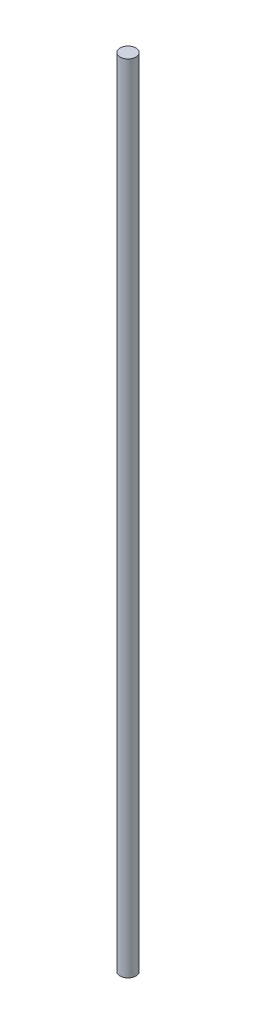
SolidWorks part; units mm, degrees
ref_plane "Front Plane" through (0, 0, 0) normal (0, 0, 1) x (1, 0, 0)
ref_plane "Top Plane" through (0, 0, 0) normal (0, 1, 0) x (1, 0, 0)
ref_plane "Right Plane" through (0, 0, 0) normal (1, 0, 0) x (0, 0, -1)
sketch "Sketch1" plane through (0, 0, 0) normal (0, 1, 0) x (1, 0, 0)
  circle A0 centre (0, 0) radius 12
  dimension "D1" = 24
extrude "Boss-Extrude1" add sketch "Sketch1" along normal blind 1200
